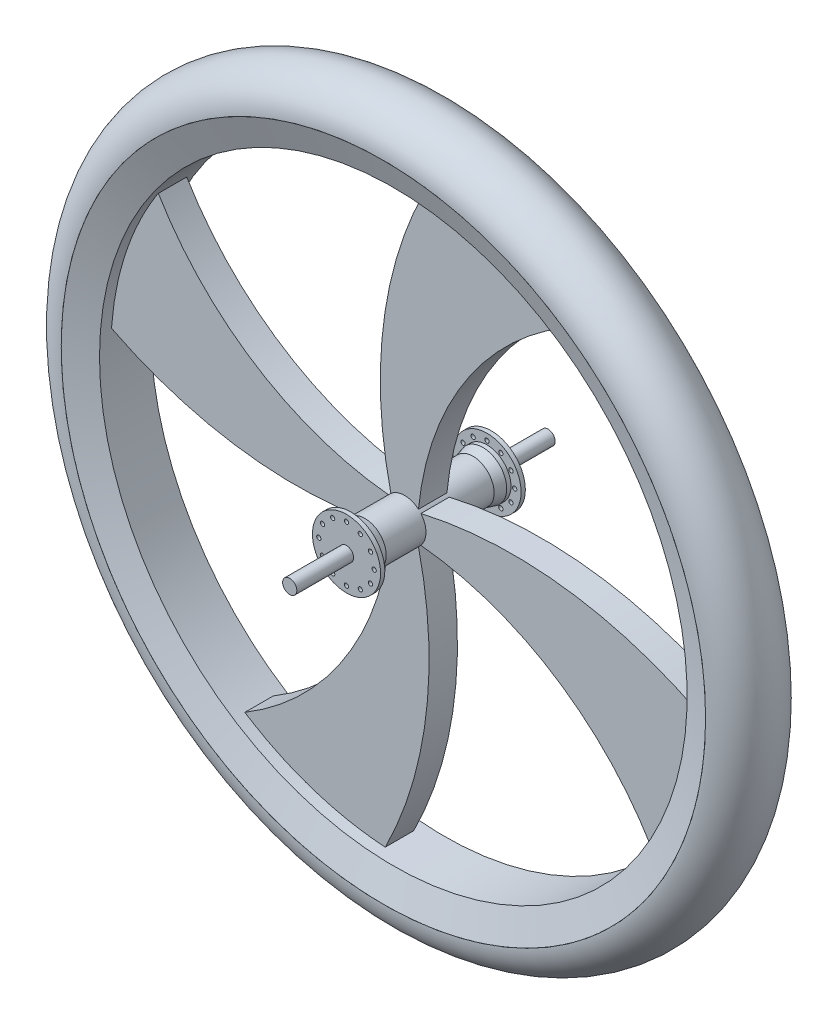
SolidWorks part; units mm, degrees
ref_plane "Front Plane" through (0, 0, 0) normal (0, 0, 1) x (1, 0, 0)
ref_plane "Top Plane" through (0, 0, 0) normal (0, 1, 0) x (1, 0, 0)
ref_plane "Right Plane" through (0, 0, 0) normal (1, 0, 0) x (0, 0, -1)
sketch "Sketch1" plane through (0, 0, 0) normal (0, 0, 1) x (1, 0, 0)
  circle A0 centre (0, 0) radius 15
extrude "Boss-Extrude1" add sketch "Sketch1" along normal blind 38
sketch "Sketch2" plane through (0, 0, 38) normal (0, 0, 1) x (1, 0, 0)
  circle A0 centre (0, 0) radius 15 construction
  circle A1 centre (0, 0) radius 15
extrude "Boss-Extrude2" add sketch "Sketch2" along normal blind 7 draft 15 draft outward yes
sketch "Sketch3" plane through (0, 0, 45) normal (0, 0, 1) x (1, 0, 0)
  circle A0 centre (0, 0) radius 16.8756 construction
  circle A1 centre (0, 0) radius 16.8756
extrude "Boss-Extrude3" add sketch "Sketch3" along normal blind 3
sketch "Sketch4" plane through (0, 0, 48) normal (0, 0, 1) x (1, 0, 0)
  circle A0 centre (0, 0) radius 24
extrude "Boss-Extrude4" add sketch "Sketch4" along normal blind 3
sketch "Sketch5" plane through (0, 0, 51) normal (0, 0, 1) x (1, 0, 0)
  circle A0 centre (0, 19.5) radius 1.5
  dimension "D1" = 19.5
extrude "Cut-Extrude3" cut sketch "Sketch5" against normal blind 3
pattern_circular "CirPattern2" count 12 every 30 about axis through (0, 0, 0) along (0, 0, 1) of "Cut-Extrude3"
mirror "Mirror1" about plane through (0, 0, 0) normal (0, 0, 1) of bodies 109
sketch "Sketch6" plane through (0, 0, 51) normal (0, 0, 1) x (1, 0, 0)
  circle A0 centre (0, 0) radius 5
extrude "Boss-Extrude5" add sketch "Sketch6" along normal blind 40
mirror "Mirror2" about plane through (0, 0, 0) normal (0, 0, 1) of bodies 111
ref_axis "Axis1" through (0, 0, 38) along (0, 0, -1)
sketch "Sketch7" plane through (0, 0, 0) normal (1, 0, 0) x (0, 0, -1)
  line L0 (0, 0) -> (0, 252) construction
  line L1 (0, 252) -> (25, 252) construction
  line L2 (25, 252) -> (25, 227) construction
  line L3 (25, 227) -> (-25, 227)
  line L5 (-18, 207) -> (18, 207)
  line L6 (18, 207) -> (25, 227)
  line L7 (0, 26.4) -> (0, -26.4) construction
  line L8 (-18, 207) -> (-25, 227)
surface "Surface-Revolve1" sketch "Sketch7" parameters "D1"=360
sketch "Sketch8" plane through (0, 0, 0) normal (0, 0, 1) x (1, 0, 0)
  arc A0 (13.7348, 206.5438) -> (112.671, 173.6498) centre (0, 0) cw
  circle A1 centre (0, 0) radius 15 construction
  arc A2 (-9.7164, 11.4277) -> (13.7348, 206.5438) centre (271.2461, 76.626) cw
  circle A3 centre (0, 0) radius 207 construction
  arc A4 (9.7164, 11.4277) -> (112.671, 173.6498) centre (221.938, -9.478) cw
  arc A5 (-9.7164, 11.4277) -> (9.7164, 11.4277) centre (0, 0) cw
  arc A6 (11.4277, 9.7164) -> (206.5438, -13.7348) centre (76.626, -271.2461) cw
  arc A7 (206.5438, -13.7348) -> (173.6498, -112.671) centre (0, 0) cw
  arc A8 (11.4277, -9.7164) -> (173.6498, -112.671) centre (-9.478, -221.938) cw
  arc A9 (11.4277, 9.7164) -> (11.4277, -9.7164) centre (0, 0) cw
  arc A10 (9.7164, -11.4277) -> (-13.7348, -206.5438) centre (-271.2461, -76.626) cw
  arc A11 (-13.7348, -206.5438) -> (-112.671, -173.6498) centre (0, 0) cw
  arc A12 (-9.7164, -11.4277) -> (-112.671, -173.6498) centre (-221.938, 9.478) cw
  arc A13 (9.7164, -11.4277) -> (-9.7164, -11.4277) centre (0, 0) cw
  arc A14 (-11.4277, -9.7164) -> (-206.5438, 13.7348) centre (-76.626, 271.2461) cw
  arc A15 (-206.5438, 13.7348) -> (-173.6498, 112.671) centre (0, 0) cw
  arc A16 (-11.4277, 9.7164) -> (-173.6498, 112.671) centre (9.478, 221.938) cw
  arc A17 (-11.4277, -9.7164) -> (-11.4277, 9.7164) centre (0, 0) cw
  point P3 (-9.7164, 11.4277)
  point P4 (-9.7164, -11.4277)
  point P5 (9.7164, -11.4277)
  point P6 (9.7164, 11.4277)
  point P38 (0, 0)
  dimension "D1" = 4
extrude "Boss-Extrude7" add sketch "Sketch8" along normal mid plane 20
sketch "Sketch9" plane through (0, 0, 0) normal (0, 1, 0) x (1, 0, 0)
  arc A0 (227, 25) -> (227, -25) centre (227, 0) cw
revolve "Revolve-Thin1" add sketch "Sketch9" angle 360 about axis through (0, 0, 38) along (0, 0, -1)
